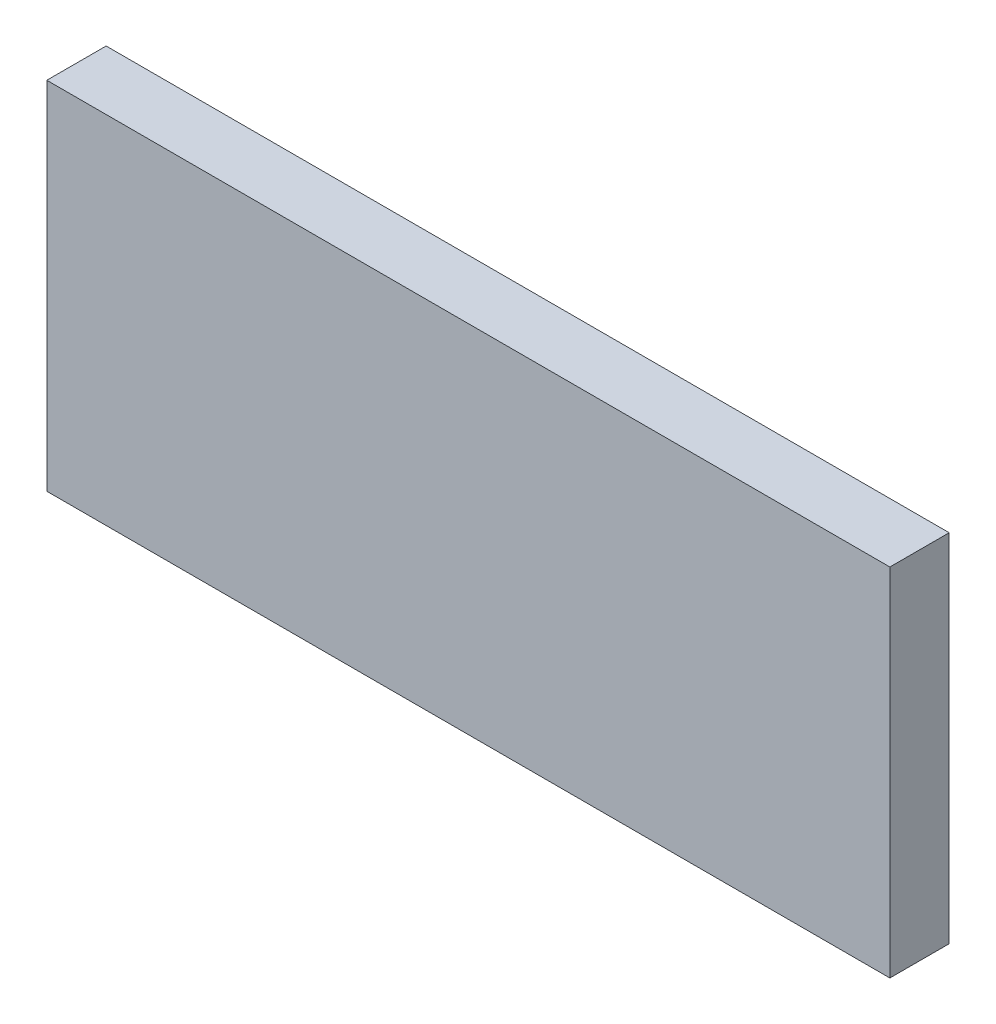
SolidWorks part; units mm, degrees
ref_plane "Alzado" through (0, 0, 0) normal (0, 0, 1) x (1, 0, 0)
ref_plane "Planta" through (0, 0, 0) normal (0, 1, 0) x (1, 0, 0)
ref_plane "Vista lateral" through (0, 0, 0) normal (1, 0, 0) x (0, 0, -1)
sketch "Croquis1" plane through (0, 0, 0) normal (0, 0, 1) x (1, 0, 0)
  line L1 (13.5, -5.7) -> (-13.5, -5.7)
  line L2 (13.5, -5.7) -> (13.5, 5.7)
  line L3 (13.5, 5.7) -> (-13.5, 5.7)
  line L4 (-13.5, -5.7) -> (-13.5, 5.7)
  line L5 (13.5, -5.7) -> (-13.5, 5.7) construction
  line L6 (13.5, 5.7) -> (-13.5, -5.7) construction
  point P0 (0, 0)
  dimension "D1" = 11.4
  dimension "D2" = 27
extrude "Saliente-Extruir1" add sketch "Croquis1" along normal blind 1.9
